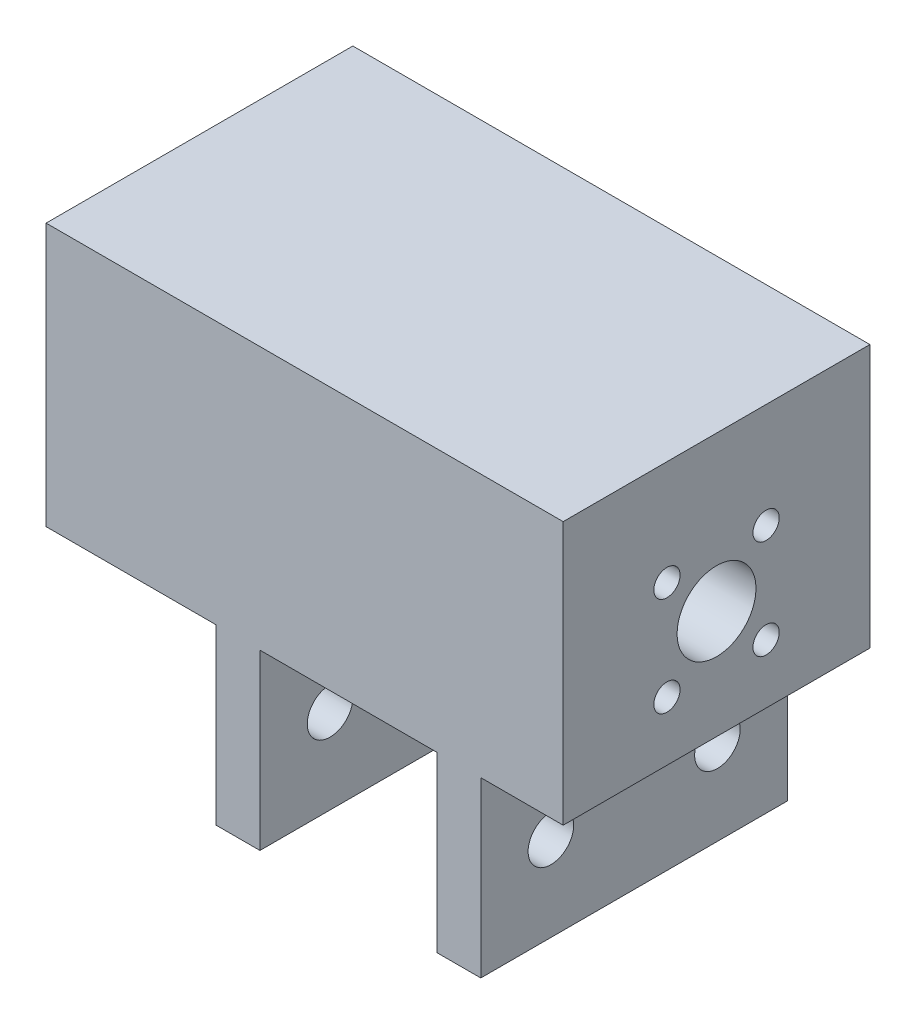
SolidWorks part; units mm, degrees
ref_plane "前视基准面" through (0, 0, 0) normal (0, 0, 1) x (1, 0, 0)
ref_plane "上视基准面" through (0, 0, 0) normal (0, 1, 0) x (1, 0, 0)
ref_plane "右视基准面" through (0, 0, 0) normal (1, 0, 0) x (0, 0, -1)
other "Configuration Table"
sketch "草图1" plane through (0, 0, 0) normal (0, 0, 1) x (1, 0, 0)
  line L0 (0, -39.6057) -> (0, 25.2485) construction
  line L9 (10.1, -34.8) -> (15.1, -34.8)
  line L10 (-24.5, -15) -> (-15.1, -15)
  line L11 (-24.5, -15) -> (-24.5, 15)
  line L12 (-24.5, 15) -> (24.5, 15)
  line L13 (24.5, -15) -> (24.5, 15)
  line L14 (-24.5, -15) -> (24.5, 15) construction
  line L15 (-24.5, 15) -> (24.5, -15) construction
  line L16 (-10.1, -15) -> (10.1, -15)
  line L17 (-15.1, -15) -> (-15.1, -34.8)
  line L18 (-15.1, -34.8) -> (-10.1, -34.8)
  line L19 (15.1, -15) -> (15.1, -34.8)
  line L21 (-10.1, -34.8) -> (-10.1, -15)
  line L22 (-10.1, -15) -> (10.1, -15)
  line L23 (10.1, -34.8) -> (10.1, -15)
  line L24 (-15.3981, -45.5587) -> (10.1, -15) construction
  line L25 (-10.1, -15) -> (18.7639, -49.5924) construction
  line L26 (-10.1, -15) -> (10.1, -15)
  line L27 (15.1, -15) -> (24.5, -15)
  point P2 (0, 0)
  point P12 (0, -27.1045)
  dimension "D1" = 49
  dimension "D2" = 30
  dimension "D3" = 19.8
  dimension "D4" = 5
  dimension "D5" = 20.2
extrude "凸台-拉伸1" add sketch "草图1" along normal blind 35 contours L19 L27 L13 L12 L11 L10 L17 L18 L21 L16 L23 L9
hole_wizard "孔1" positions "草图4" profile "草图3" legacy end condition through all
sketch "草图4" plane through (-24.5, 0, 0) normal (-1, 0, 0) x (0, 0, 1)
  line L0 (17.5, 15) -> (17.5, -15) construction
  line L1 (35, 15) -> (0, 15) construction
  line L2 (35, -15) -> (0, -15) construction
  point P0 (17.5, -2.6)
  dimension "D1" = 12.4
sketch "草图3" plane through (-24.5, -2.6, 17.5) normal (0, 1, 0) x (0, 0, 1)
  line L0 (0, 0) -> (0, 49)
  line L1 (0, 49) -> (4.5, 49)
  line L2 (4.5, 49) -> (4.5, 0)
  line L3 (4.5, 0) -> (0, 0)
  line L4 (0, 110) -> (0, -10) construction
  dimension "直径" = 9
  dimension "深度" = 49
sketch "草图12" plane through (-24.5, 0, 0) normal (-1, 0, 0) x (0, 0, 1)
  line L1 (11.8431, -8.2569) -> (23.1569, -8.2569) construction
  line L2 (11.8431, -8.2569) -> (11.8431, 3.0569) construction
  line L3 (11.8431, 3.0569) -> (23.1569, 3.0569) construction
  line L4 (23.1569, -8.2569) -> (23.1569, 3.0569) construction
  line L5 (11.8431, -8.2569) -> (23.1569, 3.0569) construction
  line L6 (11.8431, 3.0569) -> (23.1569, -8.2569) construction
  circle A0 centre (17.5, -2.6) radius 8 construction
  circle A2 centre (11.8431, 3.0569) radius 1.5
  circle A3 centre (23.1569, 3.0569) radius 1.5
  circle A4 centre (23.1569, -8.2569) radius 1.5
  circle A5 centre (11.8431, -8.2569) radius 1.5
  dimension "D1" = 16
  dimension "D2" = 3
  dimension "D3" = 3
  dimension "D4" = 3
  dimension "D5" = 3
extrude "切除-拉伸1" cut sketch "草图12" against normal through all
sketch "草图15" plane through (-24.5, 0, 0) normal (-1, 0, 0) x (0, 0, 1)
  circle A0 centre (17.5, -2.6) radius 5.2
  dimension "D1" = 10.4
extrude "切除-拉伸4" cut sketch "草图15" against normal blind 16
sketch "草图14" plane through (-24.5, 0, 0) normal (-1, 0, 0) x (0, 0, 1)
  circle A0 centre (17.5, -2.6) radius 11.75
  dimension "D1" = 23.5
extrude "切除-拉伸3" cut sketch "草图14" against normal blind 4
hole_wizard "孔2" positions "草图16" profile "草图17" legacy
sketch "草图16" plane through (-15.1, 0, 0) normal (-1, 0, 0) x (0, 0, 1)
  line L0 (35, -15) -> (0, -15) construction
  line L1 (35, -15) -> (35, -34.8) construction
  line L2 (0, -15) -> (0, -34.8) construction
  point P0 (8, -25)
  point P2 (27, -25)
  dimension "D1" = 10
  dimension "D2" = 10
  dimension "D3" = 8
  dimension "D4" = 8
sketch "草图17" plane through (-15.1, -25, 8) normal (0, 1, 0) x (0, 0, 1)
  line L0 (0, 0) -> (0, 100)
  line L1 (0, 100) -> (2.6, 100)
  line L2 (2.6, 100) -> (2.6, 0)
  line L3 (2.6, 0) -> (0, 0)
  line L4 (0, 110) -> (0, -10) construction
  dimension "直径" = 5.2
  dimension "深度" = 100
sketch "草图18" plane through (-24.5, 0, 0) normal (-1, 0, 0) x (0, 0, 1)
  line L1 (0, 15) -> (35, 15)
  line L2 (0, 15) -> (0, -15)
  line L3 (0, -15) -> (35, -15)
  line L4 (35, 15) -> (35, -15)
  circle A0 centre (17.5, -2.6) radius 11.75
extrude "凸台-拉伸2" add sketch "草图18" along normal blind 10
